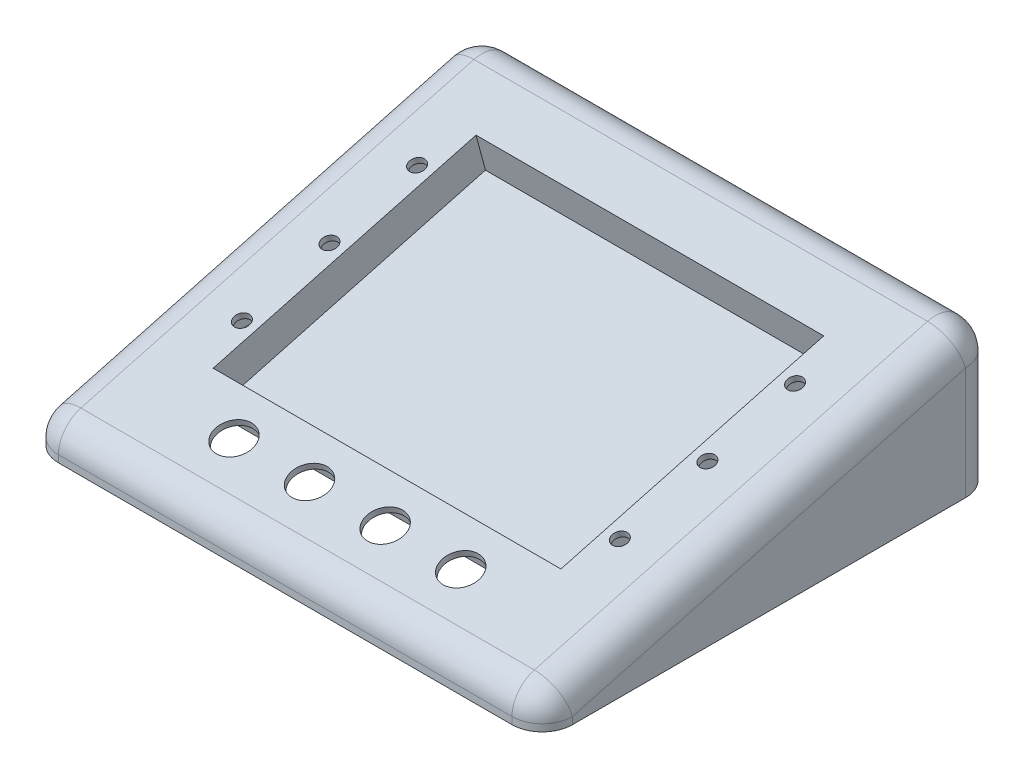
SolidWorks part; units mm, degrees
ref_plane "Front Plane" through (0, 0, 0) normal (0, 0, 1) x (1, 0, 0)
ref_plane "Top Plane" through (0, 0, 0) normal (0, 1, 0) x (1, 0, 0)
ref_plane "Right Plane" through (0, 0, 0) normal (1, 0, 0) x (0, 0, -1)
sketch "Sketch1" plane through (0, 0, 0) normal (0, 1, 0) x (1, 0, 0)
  line L1 (-85, 75) -> (85, 75)
  line L2 (-85, 75) -> (-85, -75)
  line L3 (-85, -75) -> (85, -75)
  line L4 (85, 75) -> (85, -75)
  line L5 (-85, 75) -> (85, -75) construction
  line L6 (-85, -75) -> (85, 75) construction
  point P0 (0, 0)
  dimension "D1" = 150
  dimension "D2" = 170
extrude "Boss-Extrude1" add sketch "Sketch1" along normal blind 10
sketch "Sketch2" plane through (-85, 0, 0) normal (-1, 0, 0) x (0, 0, 1)
  line L0 (-75, 10) -> (-75, 50.1924)
  line L1 (-75, 50.1924) -> (75, 10)
  line L2 (75, 10) -> (75, 0) construction
  line L3 (-75, 10) -> (75, 10) construction
  line L4 (75, 10) -> (-75, 10)
  dimension "D1" = 15
extrude "Boss-Extrude2" add sketch "Sketch2" against normal up to surface (170 mm away) up to face at (85, 5, 0)
fillet "Fillet1" radius 10 8 edges at (0, 10, 75) (85, 30.0962, 0) (-85, 30.0962, 0) (0, 50.1924, -75) (85, 5, 75) (85, 25.0962, -75) (-85, 25.0962, -75) (-85, 5, 75)
shell "Shell1" thickness 2
sketch "Sketch3" plane through (0, 28.0801, 7.524) normal (0, 0.9659, 0.2588) x (1, 0, 0)
  line L1 (-57.5, 55) -> (57.5, 55)
  line L2 (-57.5, 55) -> (-57.5, -35)
  line L3 (-57.5, -35) -> (57.5, -35)
  line L4 (57.5, 55) -> (57.5, -35)
  point P0 (0, -35)
  point P7 (57.5, 10)
  dimension "D1" = 115
  dimension "D2" = 90
  dimension "D3" = 10
extrude "Cut-Extrude1" cut sketch "Sketch3" against normal up to surface (2 mm away) up to face at (0, 27.4708, 2.0706)
sketch "Sketch4" plane through (0, 26.1483, 7.0064) normal (0, -0.9659, -0.2588) x (1, 0, 0)
  line L0 (-59.5, -57) -> (59.5, -57)
  line L1 (59.5, -57) -> (59.5, 37)
  line L2 (59.5, 37) -> (-59.5, 37)
  line L3 (-59.5, 37) -> (-59.5, -57)
  line L4 (-57.5, -55) -> (57.5, -55)
  line L5 (57.5, -55) -> (57.5, 35)
  line L6 (57.5, 35) -> (-57.5, 35)
  line L7 (-57.5, 35) -> (-57.5, -55)
  line L8 (-57.5, -55) -> (57.5, -55)
  line L9 (57.5, -55) -> (57.5, 35)
  line L10 (57.5, 35) -> (-57.5, 35)
  line L11 (-57.5, 35) -> (-57.5, -55)
  dimension "D1" = 0
  dimension "D2" = 2
extrude "Boss-Extrude3" add sketch "Sketch4" along normal blind 10
sketch "Sketch5" plane through (0, 16.489, 4.4182) normal (0, -0.9659, -0.2588) x (1, 0, 0)
  line L4 (-59.5, 37) -> (-59.5, -57)
  line L5 (-59.5, -57) -> (59.5, -57)
  line L6 (59.5, -57) -> (59.5, 37)
  line L7 (59.5, 37) -> (-59.5, 37)
  line L8 (-59.5, 37) -> (-59.5, -57)
  line L9 (-59.5, -57) -> (59.5, -57)
  line L10 (59.5, -57) -> (59.5, 37)
  line L11 (59.5, 37) -> (-59.5, 37)
  dimension "D1" = 0
extrude "Boss-Extrude4" add sketch "Sketch5" along normal blind 2
sketch "Sketch6" plane through (0, 28.0801, 7.524) normal (0, 0.9659, 0.2588) x (1, 0, 0)
  line L0 (-57.5, -35) -> (-57.5, 55) construction
  line L1 (-57.5, 55) -> (-57.5, -35) construction
  line L2 (0, -25.9381) -> (0, 25.9381) construction
  circle A0 centre (-62.5, 10) radius 2.5
  circle A1 centre (-62.5, 40) radius 2.5
  circle A2 centre (-62.5, -20) radius 2.5
  circle A3 centre (62.5, -20) radius 2.5
  circle A4 centre (62.5, 40) radius 2.5
  circle A5 centre (62.5, 10) radius 2.5
  point P9 (-57.5, 10)
  dimension "D4" = 5
  dimension "D1" = 5
  dimension "D2" = 30
  dimension "D3" = 30
extrude "Cut-Extrude2" cut sketch "Sketch6" against normal up to surface (2 mm away) up to face at (0, 27.4708, 2.0706)
sketch "Sketch7" plane through (0, 28.0801, 7.524) normal (0, 0.9659, 0.2588) x (1, 0, 0)
  line L5 (-37.5, -48.5915) -> (37.5, -48.5915) construction
  line L9 (-57.5, -35) -> (-57.5, -62.183) construction
  line L10 (-75, -62.183) -> (75, -62.183) construction
  circle A0 centre (-12.5, -48.5915) radius 6
  circle A1 centre (12.5, -48.5915) radius 6
  circle A2 centre (37.5, -48.5915) radius 6
  circle A3 centre (-37.5, -48.5915) radius 6
  point P9 (-57.5, -48.5915)
  point P12 (0, -48.5915)
  dimension "D1" = 12
  dimension "D2" = 25
  dimension "D3" = 75
  dimension "D4" = 12.5
extrude "Cut-Extrude3" cut sketch "Sketch7" against normal up to surface (2 mm away) up to face at (-62.5, 35.854, -29.2158)
sketch "Sketch9" plane through (0, 0, 0) normal (0, -1, 0) x (1, 0, 0)
  line L0 (-83, 65) -> (-83, -65) construction
  line L1 (-83, -40) -> (-73, -40)
  line L2 (-83, -40) -> (-83, -55)
  line L3 (-83, -55) -> (-73, -55)
  line L4 (-73, -40) -> (-73, -55)
  dimension "D1" = 15
  dimension "D2" = 10
  dimension "D3" = 40
extrude "Boss-Extrude5" add sketch "Sketch9" against normal blind 10
sketch "Sketch10" plane through (0, 0, 0) normal (0, -1, 0) x (1, 0, 0)
  line L8 (-75.5, -42.5) -> (-80.5, -42.5)
  line L9 (-75.5, -52.5) -> (-75.5, -42.5)
  line L10 (-80.5, -52.5) -> (-75.5, -52.5)
  line L11 (-80.5, -42.5) -> (-80.5, -52.5)
  line L12 (-75.5, -42.5) -> (-80.5, -42.5)
  line L13 (-75.5, -52.5) -> (-75.5, -42.5)
  line L14 (-80.5, -52.5) -> (-75.5, -52.5)
  line L15 (-80.5, -42.5) -> (-80.5, -52.5)
  dimension "D1" = 2.5
extrude "Cut-Extrude4" cut sketch "Sketch10" against normal blind 5
mirror "Mirror1" about plane through (0, 0, 0) normal (1, 0, 0) of "Boss-Extrude5", "Cut-Extrude4" second plane through (0, 0, 0) second plane normal (0, 0, 1)
fillet "Fillet2" radius 2 8 edges at (-73, 5, -40) (-73, 5, -55) (-73, 5, 40) (-73, 5, 55) (73, 5, -55) (73, 5, -40) (73, 5, 55) (73, 5, 40)
